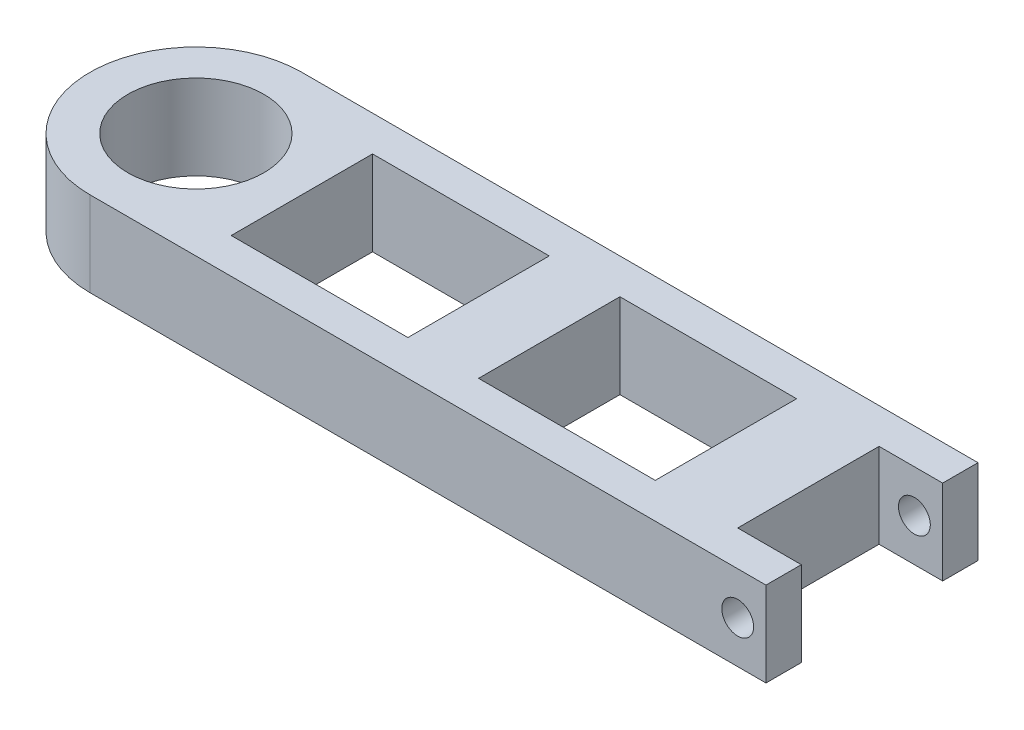
SolidWorks part; units mm, degrees
ref_plane "Front Plane" through (0, 0, 0) normal (0, 0, 1) x (1, 0, 0)
ref_plane "Top Plane" through (0, 0, 0) normal (0, 1, 0) x (1, 0, 0)
ref_plane "Right Plane" through (0, 0, 0) normal (1, 0, 0) x (0, 0, -1)
sketch "Sketch1" plane through (0, 0, 0) normal (0, 1, 0) x (1, 0, 0)
  line L0 (-135, 0) -> (-39.3333, 0) construction
  line L1 (-55, 0) -> (55, 0) construction
  line L2 (-135, 15) -> (-39.3333, 15)
  line L3 (-135, -15) -> (-39.3333, -15)
  line L4 (0, -55) -> (0, 55) construction
  line L5 (-39.3333, 15) -> (-39.3333, 10)
  line L6 (-39.3333, 10) -> (-48.3333, 10)
  line L7 (-48.3333, 10) -> (-48.3333, -10)
  line L8 (-48.3333, -10) -> (-39.3333, -10)
  line L9 (-39.3333, -10) -> (-39.3333, -15)
  line L11 (-120, 10) -> (-95, 10)
  line L12 (-120, 10) -> (-120, -10)
  line L13 (-120, -10) -> (-95, -10)
  line L14 (-95, 10) -> (-95, -10)
  line L15 (-85, 10) -> (-60, 10)
  line L16 (-85, 10) -> (-85, -10)
  line L17 (-85, -10) -> (-60, -10)
  line L18 (-60, 10) -> (-60, -10)
  arc A0 (-135, 15) -> (-135, -15) centre (-135, 0) ccw
  circle A2 centre (-135, 0) radius 9.625
  point P5 (8.75, 0)
  dimension "D1" = 9
  dimension "D14" = 19.25
  dimension "D2" = 20
  dimension "D3" = 135
  dimension "D4" = 95.6667
  dimension "D5" = 10
  dimension "D6" = 20
  dimension "D7" = 25
  dimension "D8" = 25
  dimension "D9" = 20
  dimension "D10" = 10
  dimension "D11" = 10
  dimension "D12" = 15
  dimension "D13" = 10
extrude "Boss-Extrude1" add sketch "Sketch1" along normal blind 12
sketch "Sketch2" plane through (0, 0, -15) normal (0, 0, -1) x (-1, 0, 0)
  line L0 (39.3333, 12) -> (135, 12) construction
  line L1 (39.3333, 12) -> (39.3333, 0) construction
  circle A0 centre (43.3333, 6) radius 2.25
  dimension "D1" = 4.5
  dimension "D2" = 6
  dimension "D3" = 4
extrude "Cut-Extrude1" cut sketch "Sketch2" against normal through all
